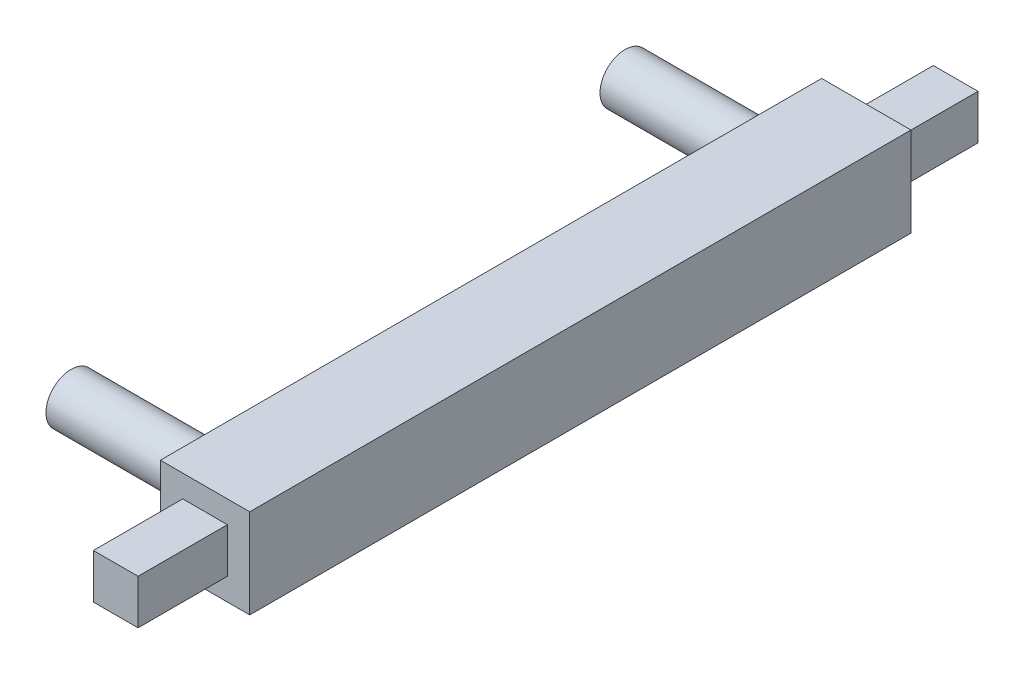
SolidWorks part; units mm, degrees
ref_plane "Front Plane" through (0, 0, 0) normal (0, 0, 1) x (1, 0, 0)
ref_plane "Top Plane" through (0, 0, 0) normal (0, 1, 0) x (1, 0, 0)
ref_plane "Right Plane" through (0, 0, 0) normal (1, 0, 0) x (0, 0, -1)
sketch "Sketch1" plane through (0, 0, 0) normal (0, 0, 1) x (1, 0, 0)
  line L1 (0, 0) -> (5, 0)
  line L2 (0, 0) -> (0, 5)
  line L3 (0, 5) -> (5, 5)
  line L4 (5, 0) -> (5, 5)
  dimension "D1" = 5
  dimension "D2" = 5
extrude "Boss-Extrude1" add sketch "Sketch1" along normal blind 37
sketch "Sketch2" plane through (0, 0, 37) normal (0, 0, 1) x (1, 0, 0)
  line L0 (0, 5) -> (0, 0) construction
  line L1 (1.25, 1.25) -> (3.75, 1.25)
  line L2 (1.25, 1.25) -> (1.25, 3.75)
  line L3 (1.25, 3.75) -> (3.75, 3.75)
  line L4 (3.75, 1.25) -> (3.75, 3.75)
  line L5 (5, 5) -> (0, 5) construction
  dimension "D1" = 2.5
  dimension "D2" = 2.5
  dimension "D3" = 1.25
  dimension "D4" = 1.25
extrude "Boss-Extrude2" add sketch "Sketch2" along normal blind 5
sketch "Sketch3" plane through (0, 0, 0) normal (0, 0, -1) x (-1, 0, 0)
  line L0 (-5, 0) -> (-5, 5) construction
  line L1 (-3.75, 1.25) -> (-1.25, 1.25)
  line L2 (-3.75, 1.25) -> (-3.75, 3.75)
  line L3 (-3.75, 3.75) -> (-1.25, 3.75)
  line L4 (-1.25, 1.25) -> (-1.25, 3.75)
  line L5 (-5, 5) -> (0, 5) construction
  dimension "D1" = 2.5
  dimension "D2" = 2.5
  dimension "D3" = 1.25
  dimension "D4" = 1.25
extrude "Boss-Extrude3" add sketch "Sketch3" along normal blind 5
sketch "Sketch4" plane through (0, 0, 0) normal (-1, 0, 0) x (0, 0, 1)
  line L0 (37, 5) -> (0, 5) construction
  line L1 (0, 1.25) -> (0, 3.75) construction
  circle A0 centre (3, 2.5) radius 1.4
  circle A1 centre (34, 2.5) radius 1.4
  dimension "D1" = 2.8
  dimension "D2" = 2.8
  dimension "D3" = 31
  dimension "D4" = 2.5
  dimension "D5" = 3
  dimension "D6" = 2.5
extrude "Boss-Extrude4" add sketch "Sketch4" along normal blind 8
